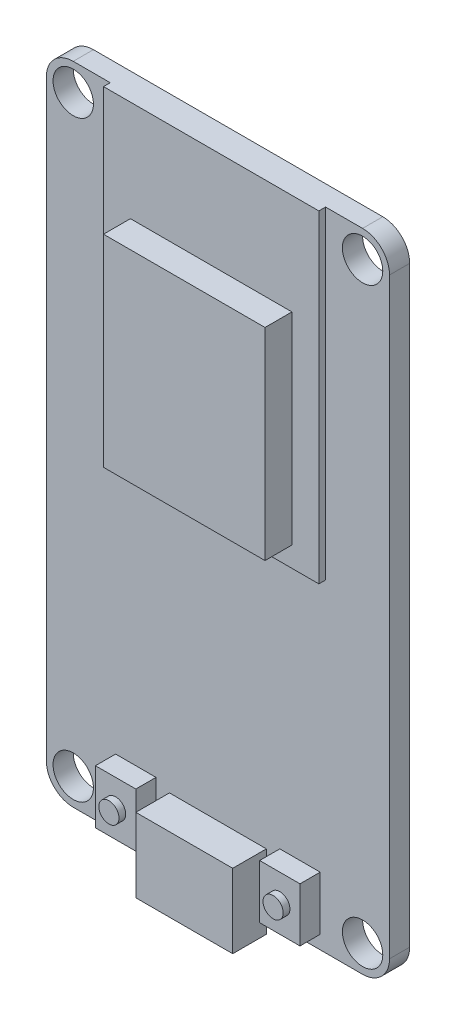
SolidWorks part; units mm, degrees
ref_plane "Front Plane" through (0, 0, 0) normal (0, 0, 1) x (1, 0, 0)
ref_plane "Top Plane" through (0, 0, 0) normal (0, 1, 0) x (1, 0, 0)
ref_plane "Right Plane" through (0, 0, 0) normal (1, 0, 0) x (0, 0, -1)
sketch "Sketch1" plane through (0, 0, 0) normal (0, 0, 1) x (1, 0, 0)
  line L1 (-12.75, 24) -> (12.75, 24)
  line L2 (-12.75, 24) -> (-12.75, -24)
  line L3 (-12.75, -24) -> (12.75, -24)
  line L4 (12.75, 24) -> (12.75, -24)
  line L5 (-12.75, 24) -> (12.75, -24) construction
  line L6 (-12.75, -24) -> (12.75, 24) construction
  point P0 (0, 0)
  dimension "D1" = 48
  dimension "D2" = 25.5
extrude "PCB" add sketch "Sketch1" along normal blind 1.5
fillet "Fillet1" radius 2 4 edges at (-12.75, -24, 0.75) (12.75, -24, 0.75) (-12.75, 24, 0.75) (12.75, 24, 0.75)
sketch "Sketch2" plane through (0, 0, 1.5) normal (0, 0, 1) x (1, 0, 0)
  circle A0 centre (-10.75, 22) radius 1.5
  circle A1 centre (10.75, 22) radius 1.5
  circle A2 centre (10.75, -22) radius 1.5
  circle A3 centre (-10.75, -22) radius 1.5
  arc A5 (12.75, 22) -> (10.75, 24) centre (10.75, 22) ccw construction
  arc A6 (-12.75, -22) -> (-10.75, -24) centre (-10.75, -22) ccw construction
  arc A7 (10.75, -24) -> (12.75, -22) centre (10.75, -22) ccw construction
  arc A8 (-10.75, 24) -> (-12.75, 22) centre (-10.75, 22) ccw construction
  point P12 (0, 0)
  point P22 (-56.1312, 21.2315)
  dimension "D1" = 3
extrude "Screw holes" cut sketch "Sketch2" against normal through all both and the other way through all
sketch "Sketch3" plane through (0, 0, 1.5) normal (0, 0, 1) x (1, 0, 0)
  line L0 (10.75, 24) -> (-10.75, 24) construction
  line L1 (-8, 24) -> (8, 24)
  line L2 (-8, 24) -> (-8, 0)
  line L3 (-8, 0) -> (8, 0)
  line L4 (8, 24) -> (8, 0)
  line L5 (-8, 24) -> (8, 0) construction
  line L6 (-8, 0) -> (8, 24) construction
  point P0 (0, 12)
  point P5 (0, 0)
  dimension "D1" = 16
  dimension "D2" = 24
extrude "ESP PCB" add sketch "Sketch3" along normal blind 0.5
sketch "Sketch4" plane through (0, 0, 2) normal (0, 0, 1) x (1, 0, 0)
  line L0 (-8, 0) -> (8, 0) construction
  line L1 (-6, 16.5) -> (6, 16.5)
  line L2 (-6, 16.5) -> (-6, 1.5)
  line L3 (-6, 1.5) -> (6, 1.5)
  line L4 (6, 16.5) -> (6, 1.5)
  line L5 (-6, 16.5) -> (6, 1.5) construction
  line L6 (-6, 1.5) -> (6, 16.5) construction
  point P0 (0, 9)
  point P5 (0, 0)
  dimension "D1" = 15
  dimension "D2" = 12
  dimension "D3" = 1.5
extrude "RF Casing" add sketch "Sketch4" along normal blind 2
sketch "Sketch5" plane through (0, 0, 1.5) normal (0, 0, 1) x (1, 0, 0)
  line L0 (-10.75, -24) -> (10.75, -24) construction
  line L1 (-3.6, -19.5) -> (3.6, -19.5)
  line L2 (-3.6, -19.5) -> (-3.6, -25)
  line L3 (-3.6, -25) -> (3.6, -25)
  line L4 (3.6, -19.5) -> (3.6, -25)
  line L5 (-3.6, -19.5) -> (3.6, -25) construction
  line L6 (-3.6, -25) -> (3.6, -19.5) construction
  point P0 (0, -22.25)
  point P5 (0, 0)
  dimension "D1" = 7.2
  dimension "D2" = 5.5
  dimension "D3" = 4.5
extrude "USB Port" add sketch "Sketch5" along normal blind 2.5
sketch "Sketch6" plane through (0, 0, 1.5) normal (0, 0, 1) x (1, 0, 0)
  line L0 (-3.6, -19.5) -> (-3.6, -25) construction
  line L1 (-7.6, -19) -> (-4.6, -19)
  line L2 (-7.6, -19) -> (-7.6, -23)
  line L3 (-7.6, -23) -> (-4.6, -23)
  line L4 (-4.6, -19) -> (-4.6, -23)
  line L9 (-10.75, -24) -> (-3.6, -24) construction
  line L10 (0, -2.2) -> (0, 2.2) construction
  line L11 (7.6, -23) -> (4.6, -23)
  line L12 (4.6, -19) -> (4.6, -23)
  line L13 (7.6, -19) -> (4.6, -19)
  line L14 (7.6, -19) -> (7.6, -23)
  dimension "D1" = 3
  dimension "D2" = 4
  dimension "D3" = 1
  dimension "D4" = 1
extrude "Button Bottom" add sketch "Sketch6" along normal blind 1.5
sketch "Sketch7" plane through (0, 0, 3) normal (0, 0, 1) x (1, 0, 0)
  line L0 (-7.6, -23) -> (-4.6, -23) construction
  line L1 (-4.6, -23) -> (-4.6, -19) construction
  line L2 (4.6, -23) -> (7.6, -23) construction
  circle A0 centre (-6.1, -21) radius 0.75
  circle A1 centre (6.1, -21) radius 0.75
  point P4 (0, 0)
  point P7 (-6.1, -23)
  point P10 (-4.6, -21)
  point P11 (0, 0)
  point P14 (6.1, -23)
  dimension "D1" = 1.5
extrude "Button Top" add sketch "Sketch7" along normal blind 0.5
